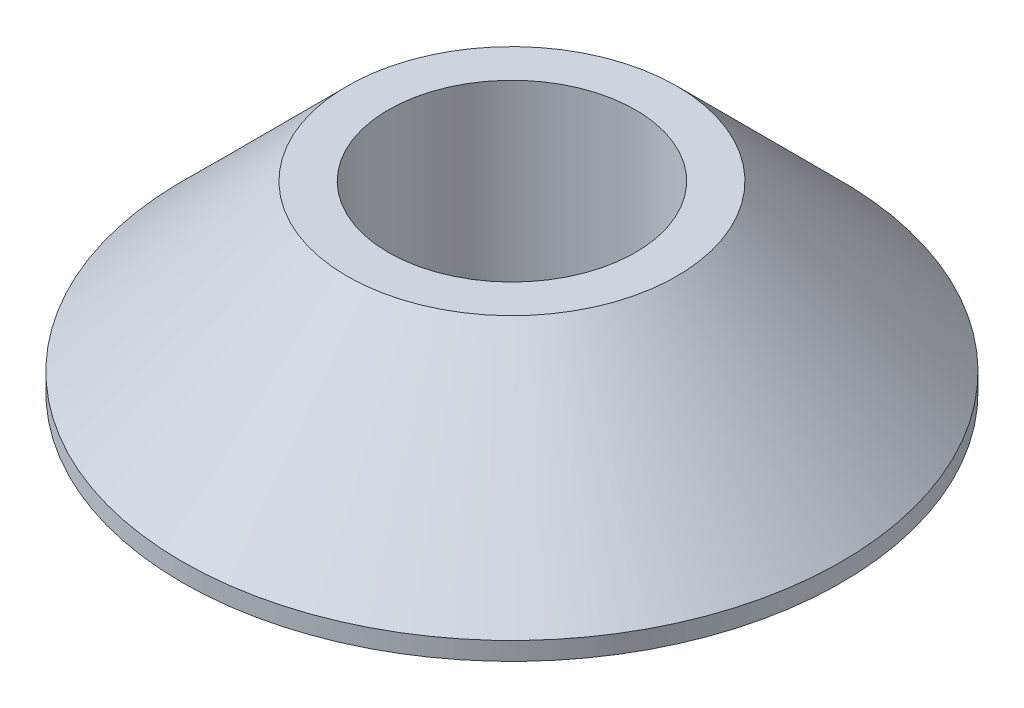
SolidWorks part; units mm, degrees
ref_plane "Front Plane" through (0, 0, 0) normal (0, 0, 1) x (1, 0, 0)
ref_plane "Top Plane" through (0, 0, 0) normal (0, 1, 0) x (1, 0, 0)
ref_plane "Right Plane" through (0, 0, 0) normal (1, 0, 0) x (0, 0, -1)
sketch "Sketch1" plane through (0, 0, 0) normal (0, 1, 0) x (1, 0, 0)
  circle A0 centre (0, 0) radius 12.7
  dimension "D1" = 25.4
extrude "Boss-Extrude1" add sketch "Sketch1" along normal blind 0.6985
sketch "Sketch2" plane through (0, 0.6985, 0) normal (0, 1, 0) x (1, 0, 0)
  circle A1 centre (0, 0) radius 12.7
  circle A2 centre (0, 0) radius 12.7
  dimension "D1" = 0
extrude "Boss-Extrude2" add sketch "Sketch2" along normal blind 6.35 draft 45
sketch "Sketch3" plane through (0, 7.0485, 0) normal (0, 1, 0) x (1, 0, 0)
  circle A0 centre (0, 0) radius 4.7625
  dimension "D1" = 9.525
extrude "Cut-Extrude1" cut sketch "Sketch3" against normal through all
